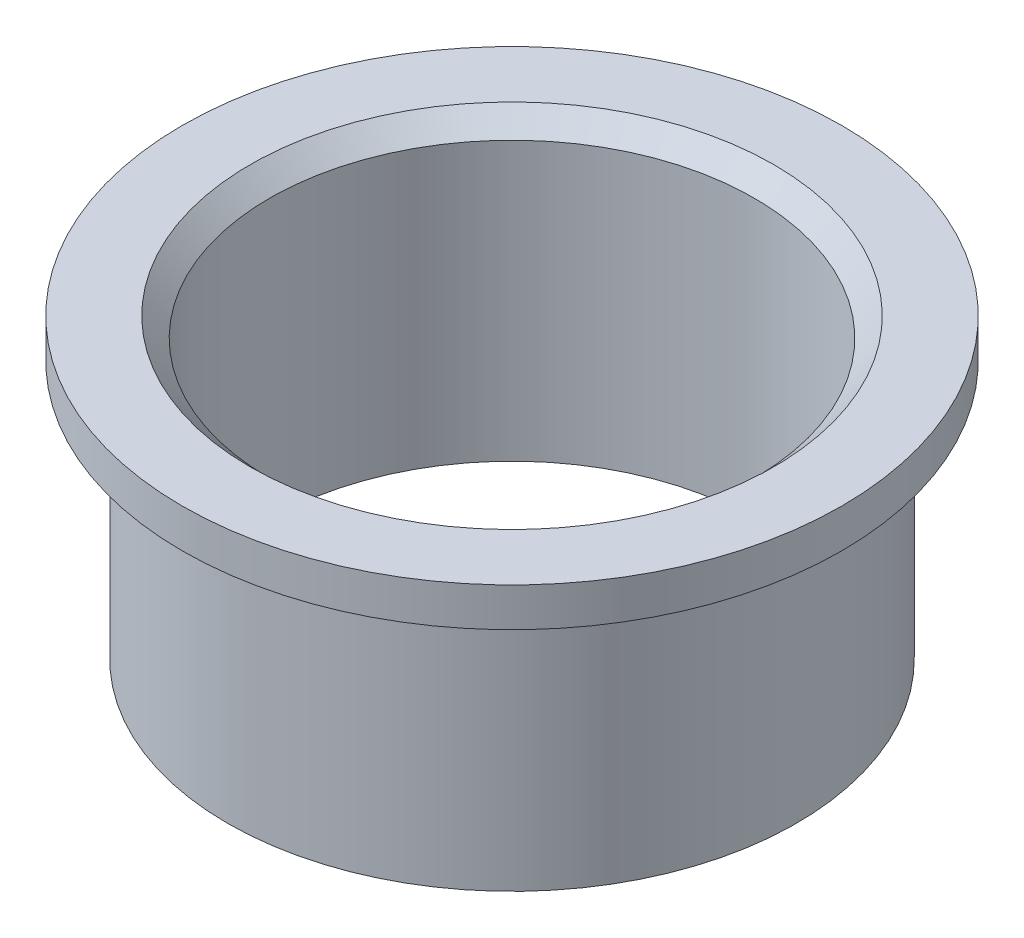
SolidWorks part; units mm, degrees
ref_plane "Piano frontale" through (0, 0, 0) normal (0, 0, 1) x (1, 0, 0)
ref_plane "Piano superiore" through (0, 0, 0) normal (0, 1, 0) x (1, 0, 0)
ref_plane "Piano destro" through (0, 0, 0) normal (1, 0, 0) x (0, 0, -1)
sketch "Schizzo1" plane through (0, 0, 0) normal (0, 0, 1) x (1, 0, 0)
  line L0 (-51, 0) -> (-40.5, 0)
  line L1 (-40.5, 0) -> (-37.5, -3)
  line L2 (-37.5, -3) -> (-37.5, -46)
  line L3 (-37.5, -46) -> (-44, -46)
  line L4 (-44, -46) -> (-44, -6)
  line L5 (-44, -6) -> (-51, -6)
  line L6 (-51, -6) -> (-51, 0)
  line L7 (0, 0) -> (0, -33.5138) construction
  point P3 (-40.5958, 0)
  point P11 (0, 0)
  dimension "D1" = 102
  dimension "D2" = 88
  dimension "D3" = 75
  dimension "D4" = 45
  dimension "D5" = 3
  dimension "D6" = 6
  dimension "D7" = 40
revolve "Rivoluzione1" add sketch "Schizzo1" angle 360 about L7
